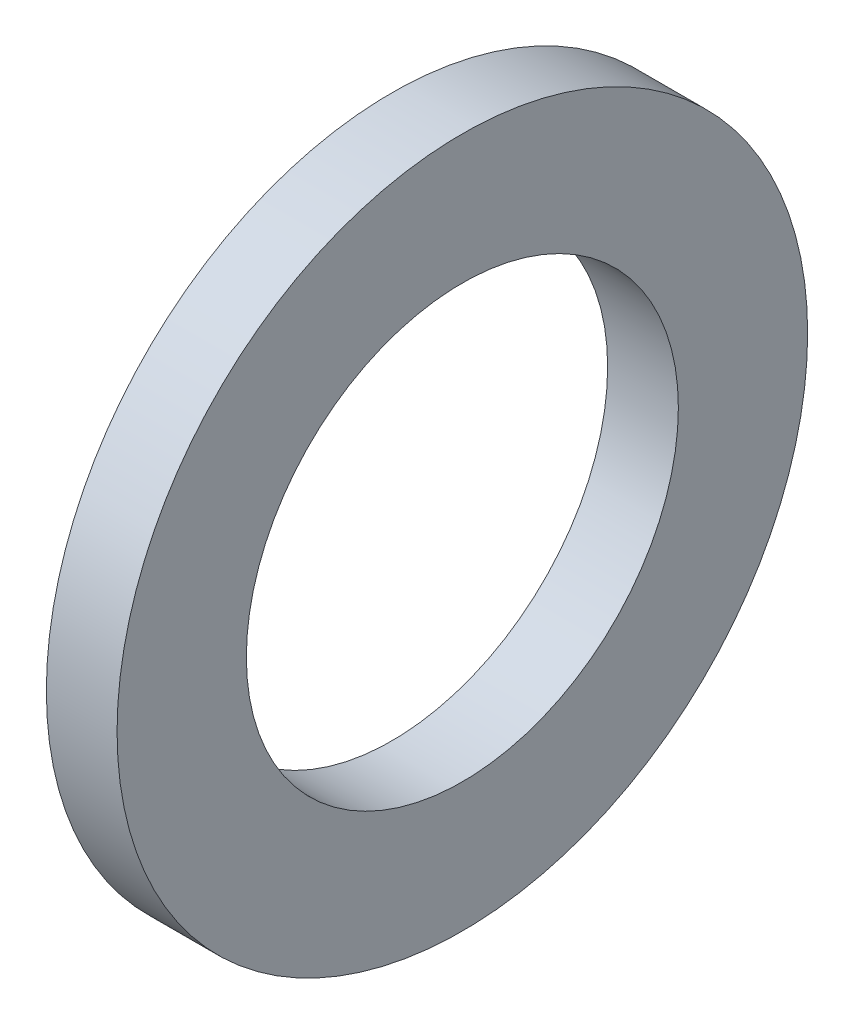
SolidWorks part; units mm, degrees
material "1060 Alloy"
ref_plane "Front Plane" through (0, 0, 0) normal (0, 0, 1) x (1, 0, 0)
ref_plane "Top Plane" through (0, 0, 0) normal (0, 1, 0) x (1, 0, 0)
ref_plane "Right Plane" through (0, 0, 0) normal (1, 0, 0) x (0, 0, -1)
sketch "Sketch3" plane through (0, 0, 0) normal (0, 0, 1) x (1, 0, 0)
  line L0 (-0.8128, 0) -> (0.8128, 0) construction
  line L1 (0, -7.9375) -> (0, 7.9375) construction
  line L2 (0, -4.9657) -> (0, 4.9657) construction
  point P4 (0, 0)
  point P8 (0, 0)
  point P11 (0, 0)
sketch "Sketch1" plane through (0, 0, 0) normal (1, 0, 0) x (0, 0, -1)
  circle A0 centre (0, 0) radius 7.9375
  circle A1 centre (0, 0) radius 4.9657
extrude "Boss-Extrude1" add sketch "Sketch1" along normal mid plane 1.6256
equation "\"D1@Boss-Extrude1\" = \"Thickness@Sketch3\""
